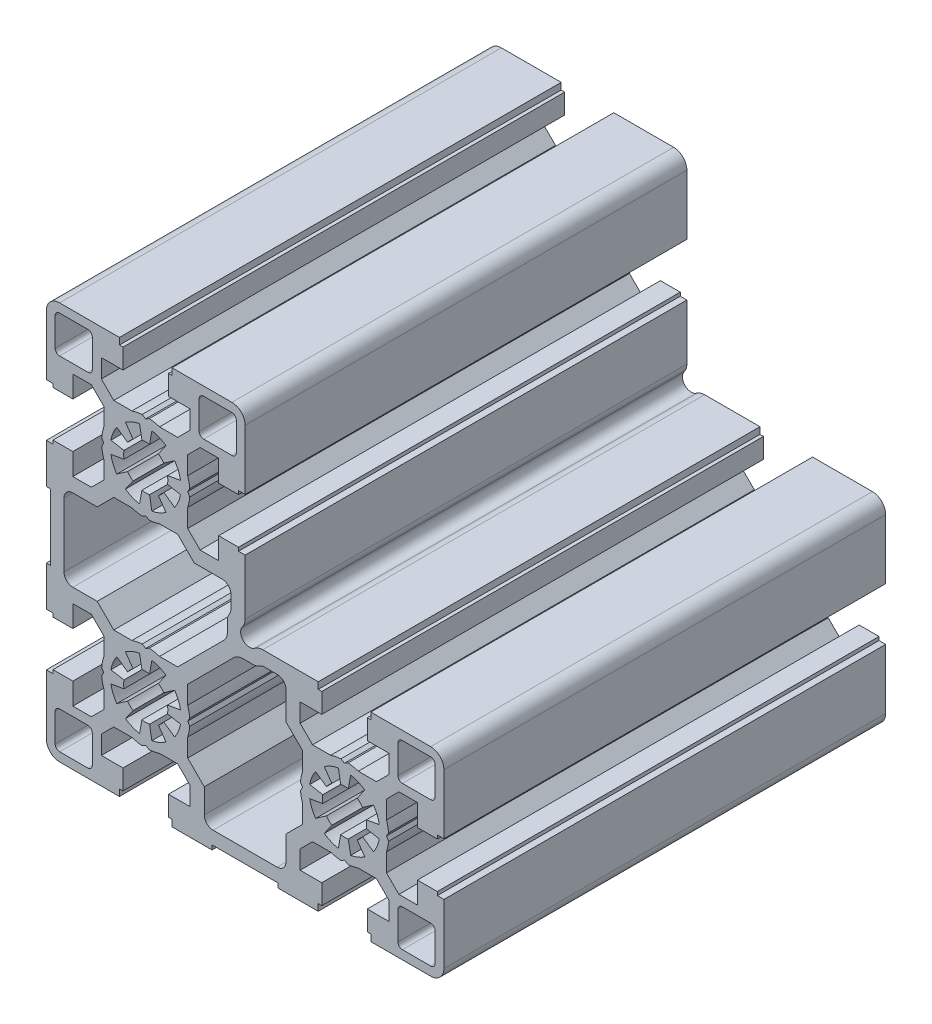
SolidWorks part; units mm, degrees
material "3.1355 (EN-AW 2024)"
ref_plane "Спереди" through (0, 0, 0) normal (0, 0, 1) x (1, 0, 0)
ref_plane "Сверху" through (0, 0, 0) normal (0, 1, 0) x (1, 0, 0)
ref_plane "Справа" through (0, 0, 0) normal (1, 0, 0) x (0, 0, -1)
sketch "Model" plane through (0, 0, 0) normal (0, 0, 1) x (1, 0, 0)
  line L512 (41.0101, -11.3899) -> (34.6101, -11.3899)
  line L513 (33.6101, -10.3899) -> (33.6101, -3.9899)
  line L514 (34.6101, -2.9899) -> (41.0101, -2.9899)
  line L515 (42.0101, -3.9899) -> (42.0101, -10.3899)
  line L516 (-43.9899, -42.9899) -> (-43.9899, -36.5899)
  line L517 (-42.9899, -35.5899) -> (-36.5899, -35.5899)
  line L518 (-35.5899, -36.5899) -> (-35.5899, -42.9899)
  line L519 (-36.5899, -43.9899) -> (-42.9899, -43.9899)
  line L520 (-19.3942, -20.6221) -> (-16.9367, -18.9013)
  line L521 (-15.6115, -22.1008) -> (-18.5659, -22.6217)
  line L522 (-18.5659, -24.3582) -> (-15.6115, -24.8791)
  line L523 (-16.9367, -28.0786) -> (-19.3942, -26.3578)
  line L524 (-20.6221, -27.5857) -> (-18.9013, -30.0432)
  line L525 (-22.1008, -31.3684) -> (-22.6217, -28.414)
  line L526 (-24.3582, -28.414) -> (-24.8791, -31.3684)
  line L527 (-28.0786, -30.0432) -> (-26.3578, -27.5857)
  line L528 (-27.5857, -26.3578) -> (-30.0432, -28.0786)
  line L529 (-31.3684, -24.8791) -> (-28.414, -24.3582)
  line L530 (-28.414, -22.6217) -> (-31.3684, -22.1008)
  line L531 (-30.0432, -18.9013) -> (-27.5857, -20.6221)
  line L532 (-26.3578, -19.3942) -> (-28.0786, -16.9367)
  line L533 (-24.8791, -15.6115) -> (-24.3582, -18.5659)
  line L534 (-22.6217, -18.5659) -> (-22.1008, -15.6115)
  line L535 (-18.9013, -16.9367) -> (-20.6221, -19.3942)
  line L536 (-10.3899, 42.0101) -> (-3.9899, 42.0101)
  line L537 (-2.9899, 41.0101) -> (-2.9899, 34.6101)
  line L538 (-3.9899, 33.6101) -> (-10.3899, 33.6101)
  line L539 (-11.3899, 34.6101) -> (-11.3899, 41.0101)
  line L540 (-20.6221, 17.4143) -> (-18.9013, 14.9568)
  line L541 (-22.1008, 13.6316) -> (-22.6217, 16.586)
  line L542 (-24.3582, 16.586) -> (-24.8791, 13.6316)
  line L543 (-28.0786, 14.9568) -> (-26.3578, 17.4143)
  line L544 (-27.5857, 18.6422) -> (-30.0432, 16.9214)
  line L545 (-31.3684, 20.1209) -> (-28.414, 20.6418)
  line L546 (-28.414, 22.3783) -> (-31.3684, 22.8992)
  line L547 (-30.0432, 26.0987) -> (-27.5857, 24.3779)
  line L548 (-26.3578, 25.6058) -> (-28.0786, 28.0633)
  line L549 (-24.8791, 29.3885) -> (-24.3582, 26.4341)
  line L550 (-22.6217, 26.4341) -> (-22.1008, 29.3885)
  line L551 (-18.9013, 28.0633) -> (-20.6221, 25.6058)
  line L552 (-19.3942, 24.3779) -> (-16.9367, 26.0987)
  line L553 (-15.6115, 22.8992) -> (-18.5659, 22.3783)
  line L554 (-18.5659, 20.6418) -> (-15.6115, 20.1209)
  line L555 (-16.9367, 16.9214) -> (-19.3942, 18.6422)
  line L556 (-42.9899, 42.0101) -> (-36.5899, 42.0101)
  line L557 (-35.5899, 41.0101) -> (-35.5899, 34.6101)
  line L558 (-36.5899, 33.6101) -> (-42.9899, 33.6101)
  line L559 (-43.9899, 34.6101) -> (-43.9899, 41.0101)
  line L560 (-13.9899, -16.2527) -> (-3.6059, -5.8686)
  line L561 (-1.4846, -4.9899) -> (0.9237, -4.9899)
  line L562 (1.916, -4.7264) -> (2.3937, -4.4535)
  line L563 (3.386, -4.1899) -> (6.2596, -4.1899)
  line L564 (8.2596, -6.1899) -> (8.2596, -12.5023)
  line L565 (8.2596, -12.5023) -> (12.0101, -16.2527)
  line L566 (12.0101, -16.2527) -> (12.0101, -20.3675)
  line L567 (11.5428, -22.6807) -> (12.0101, -23.4899)
  line L568 (12.0101, -23.4899) -> (11.5428, -24.2992)
  line L569 (12.0101, -26.6124) -> (12.0101, -30.7272)
  line L570 (12.0101, -30.7272) -> (8.2596, -34.4776)
  line L571 (8.2596, -34.4776) -> (8.2596, -39.9899)
  line L572 (6.2596, -41.9899) -> (-8.2399, -41.9899)
  line L573 (-10.2399, -39.9899) -> (-10.2399, -34.4772)
  line L574 (-10.2399, -34.4772) -> (-13.9899, -30.7272)
  line L575 (-13.9899, -30.7272) -> (-13.9899, -26.6124)
  line L576 (-13.5227, -24.2992) -> (-13.9899, -23.4899)
  line L577 (-13.9899, -23.4899) -> (-13.5227, -22.6807)
  line L578 (-13.9899, -20.3675) -> (-13.9899, -16.2527)
  line L579 (-23.4899, -13.9899) -> (-24.2992, -13.5227)
  line L580 (-26.6124, -13.9899) -> (-30.7272, -13.9899)
  line L581 (-30.7272, -13.9899) -> (-34.4772, -10.2399)
  line L582 (-34.4772, -10.2399) -> (-39.9899, -10.2399)
  line L583 (-41.9899, -8.2399) -> (-41.9899, 6.2596)
  line L584 (-39.9899, 8.2596) -> (-34.4776, 8.2596)
  line L585 (-34.4776, 8.2596) -> (-30.7272, 12.0101)
  line L586 (-30.7272, 12.0101) -> (-26.6124, 12.0101)
  line L587 (-24.2992, 11.5428) -> (-23.4899, 12.0101)
  line L588 (-23.4899, 12.0101) -> (-22.6807, 11.5428)
  line L589 (-20.3675, 12.0101) -> (-16.2527, 12.0101)
  line L590 (-16.2527, 12.0101) -> (-12.5023, 8.2596)
  line L591 (-12.5023, 8.2596) -> (-6.1899, 8.2596)
  line L592 (-4.1899, 6.2596) -> (-4.1899, 3.386)
  line L593 (-4.4535, 2.3937) -> (-4.7264, 1.916)
  line L594 (-4.9899, 0.9237) -> (-4.9899, -1.4846)
  line L595 (-5.8686, -3.6059) -> (-16.2527, -13.9899)
  line L596 (-16.2527, -13.9899) -> (-20.3675, -13.9899)
  line L597 (-22.6807, -13.5227) -> (-23.4899, -13.9899)
  line L598 (24.3779, -27.5857) -> (26.0987, -30.0432)
  line L599 (22.8992, -31.3684) -> (22.3783, -28.414)
  line L600 (20.6418, -28.414) -> (20.1209, -31.3684)
  line L601 (16.9214, -30.0432) -> (18.6422, -27.5857)
  line L602 (17.4143, -26.3578) -> (14.9568, -28.0786)
  line L603 (13.6316, -24.8791) -> (16.586, -24.3582)
  line L604 (16.586, -22.6217) -> (13.6316, -22.1008)
  line L605 (14.9568, -18.9013) -> (17.4143, -20.6221)
  line L606 (18.6422, -19.3942) -> (16.9214, -16.9367)
  line L607 (20.1209, -15.6115) -> (20.6418, -18.5659)
  line L608 (22.3783, -18.5659) -> (22.8992, -15.6115)
  line L609 (26.0987, -16.9367) -> (24.3779, -19.3942)
  line L610 (25.6058, -20.6221) -> (28.0633, -18.9013)
  line L611 (29.3885, -22.1008) -> (26.4341, -22.6217)
  line L612 (26.4341, -24.3582) -> (29.3885, -24.8791)
  line L613 (28.0633, -28.0786) -> (25.6058, -26.3578)
  line L614 (41.0101, -43.9899) -> (34.6101, -43.9899)
  line L615 (33.6101, -42.9899) -> (33.6101, -36.5899)
  line L616 (34.6101, -35.5899) -> (41.0101, -35.5899)
  line L617 (42.0101, -36.5899) -> (42.0101, -42.9899)
  line L618 (38.0101, -18.3399) -> (42.5101, -18.3399)
  line L619 (42.5101, -18.3399) -> (42.5101, -17.5399)
  line L620 (42.5101, -17.5399) -> (44.0101, -17.5399)
  line L621 (44.0101, -17.5399) -> (44.0101, -3.9897)
  line L622 (41.0101, -0.9899) -> (27.4601, -0.9899)
  line L623 (27.4601, -0.9899) -> (27.4601, -2.4899)
  line L624 (27.4601, -2.4899) -> (26.6601, -2.4899)
  line L625 (26.6601, -2.4899) -> (26.6601, -6.9899)
  line L626 (26.6601, -6.9899) -> (31.5601, -6.9899)
  line L627 (31.5601, -6.9899) -> (31.5601, -11.1772)
  line L628 (31.5601, -11.1772) -> (28.7473, -13.9899)
  line L629 (28.7473, -13.9899) -> (24.6325, -13.9899)
  line L630 (22.3193, -13.5227) -> (21.5101, -13.9899)
  line L631 (21.5101, -13.9899) -> (20.7008, -13.5227)
  line L632 (18.3876, -13.9899) -> (14.2728, -13.9899)
  line L633 (14.2728, -13.9899) -> (11.4601, -11.1772)
  line L634 (11.4601, -11.1772) -> (11.4601, -6.9899)
  line L635 (11.4601, -6.9899) -> (16.3601, -6.9899)
  line L636 (16.3601, -6.9899) -> (16.3601, -2.4899)
  line L637 (16.3601, -2.4899) -> (15.5601, -2.4899)
  line L638 (15.5601, -2.4899) -> (15.5601, -0.9899)
  line L639 (15.5601, -0.9899) -> (3.0134, -0.9899)
  line L640 (-0.9899, 3.0134) -> (-0.9899, 15.5601)
  line L641 (-0.9899, 15.5601) -> (-2.4899, 15.5601)
  line L642 (-2.4899, 15.5601) -> (-2.4899, 16.3601)
  line L643 (-2.4899, 16.3601) -> (-6.9899, 16.3601)
  line L644 (-6.9899, 16.3601) -> (-6.9899, 11.4601)
  line L645 (-6.9899, 11.4601) -> (-11.1772, 11.4601)
  line L646 (-11.1772, 11.4601) -> (-13.9899, 14.2728)
  line L647 (-13.9899, 14.2728) -> (-13.9899, 18.3876)
  line L648 (-13.5227, 20.7008) -> (-13.9899, 21.5101)
  line L649 (-13.9899, 21.5101) -> (-13.5227, 22.3193)
  line L650 (-13.9899, 24.6325) -> (-13.9899, 28.7473)
  line L651 (-13.9899, 28.7473) -> (-11.1772, 31.5601)
  line L652 (-11.1772, 31.5601) -> (-6.9899, 31.5601)
  line L653 (-6.9899, 31.5601) -> (-6.9899, 26.6601)
  line L654 (-6.9899, 26.6601) -> (-2.4899, 26.6601)
  line L655 (-2.4899, 26.6601) -> (-2.4899, 27.4601)
  line L656 (-2.4899, 27.4601) -> (-0.9899, 27.4601)
  line L657 (-0.9899, 27.4601) -> (-0.9899, 41.0101)
  line L658 (-3.9899, 44.0101) -> (-17.5399, 44.0101)
  line L659 (-17.5399, 44.0101) -> (-17.5399, 42.5101)
  line L660 (-17.5399, 42.5101) -> (-18.3399, 42.5101)
  line L661 (-18.3399, 42.5101) -> (-18.3399, 38.0101)
  line L662 (-18.3399, 38.0101) -> (-13.4399, 38.0101)
  line L663 (-13.4399, 38.0101) -> (-13.4399, 33.8228)
  line L664 (-13.4399, 33.8228) -> (-16.2527, 31.0101)
  line L665 (-16.2527, 31.0101) -> (-20.3675, 31.0101)
  line L666 (-22.6807, 31.4773) -> (-23.4899, 31.0101)
  line L667 (-23.4899, 31.0101) -> (-24.2992, 31.4773)
  line L668 (-26.6124, 31.0101) -> (-30.7272, 31.0101)
  line L669 (-30.7272, 31.0101) -> (-33.5399, 33.8228)
  line L670 (-33.5399, 33.8228) -> (-33.5399, 38.0101)
  line L671 (-33.5399, 38.0101) -> (-28.6399, 38.0101)
  line L672 (-28.6399, 38.0101) -> (-28.6399, 42.5101)
  line L673 (-28.6399, 42.5101) -> (-29.4399, 42.5101)
  line L674 (-29.4399, 42.5101) -> (-29.4399, 44.0101)
  line L675 (-29.4399, 44.0101) -> (-42.9899, 44.0101)
  line L676 (-45.9899, 41.0101) -> (-45.9899, 27.4601)
  line L677 (-45.9899, 27.4601) -> (-44.4899, 27.4601)
  line L678 (-44.4899, 27.4601) -> (-44.4899, 26.6601)
  line L679 (-44.4899, 26.6601) -> (-39.9899, 26.6601)
  line L680 (-39.9899, 26.6601) -> (-39.9899, 31.5601)
  line L681 (-39.9899, 31.5601) -> (-35.8027, 31.5601)
  line L682 (-35.8027, 31.5601) -> (-32.9899, 28.7473)
  line L683 (-32.9899, 28.7473) -> (-32.9899, 24.6325)
  line L684 (-33.4572, 22.3193) -> (-32.9899, 21.5101)
  line L685 (-32.9899, 21.5101) -> (-33.4572, 20.7008)
  line L686 (-32.9899, 18.3876) -> (-32.9899, 14.2728)
  line L687 (-32.9899, 14.2728) -> (-35.8027, 11.4601)
  line L688 (-35.8027, 11.4601) -> (-39.9899, 11.4601)
  line L689 (-39.9899, 11.4601) -> (-39.9899, 16.3601)
  line L690 (-39.9899, 16.3601) -> (-44.4899, 16.3601)
  line L691 (-44.4899, 16.3601) -> (-44.4899, 15.5601)
  line L692 (-44.4899, 15.5601) -> (-45.9899, 15.5601)
  line L693 (-45.9899, 15.5601) -> (-45.9899, 6.5101)
  line L694 (-45.9899, 6.5101) -> (-44.9899, 6.5101)
  line L695 (-44.9899, 6.5101) -> (-44.9899, -8.4899)
  line L696 (-44.9899, -8.4899) -> (-45.9899, -8.4899)
  line L697 (-45.9899, -8.4899) -> (-45.9899, -17.5399)
  line L698 (-45.9899, -17.5399) -> (-44.4899, -17.5399)
  line L699 (-44.4899, -17.5399) -> (-44.4899, -18.3399)
  line L700 (-44.4899, -18.3399) -> (-39.9899, -18.3399)
  line L701 (-39.9899, -18.3399) -> (-39.9899, -13.4399)
  line L702 (-39.9899, -13.4399) -> (-35.8027, -13.4399)
  line L703 (-35.8027, -13.4399) -> (-32.9899, -16.2527)
  line L704 (-32.9899, -16.2527) -> (-32.9899, -20.3675)
  line L705 (-33.4576, -22.6807) -> (-32.9904, -23.4899)
  line L706 (-32.9904, -23.4899) -> (-33.4576, -24.2992)
  line L707 (-32.9899, -26.6138) -> (-32.9899, -30.7272)
  line L708 (-32.9899, -30.7272) -> (-35.8027, -33.5399)
  line L709 (-35.8027, -33.5399) -> (-39.9899, -33.5399)
  line L710 (-39.9899, -33.5399) -> (-39.9899, -28.6399)
  line L711 (-39.9899, -28.6399) -> (-44.4899, -28.6399)
  line L712 (-44.4899, -28.6399) -> (-44.4899, -29.4399)
  line L713 (-44.4899, -29.4399) -> (-45.9899, -29.4399)
  line L714 (-45.9899, -29.4399) -> (-45.9899, -42.9899)
  line L715 (-42.9899, -45.9899) -> (-29.4399, -45.9899)
  line L716 (-29.4399, -45.9899) -> (-29.4399, -44.4899)
  line L717 (-29.4399, -44.4899) -> (-28.6399, -44.4899)
  line L718 (-28.6399, -44.4899) -> (-28.6399, -39.9899)
  line L719 (-28.6399, -39.9899) -> (-33.5399, -39.9899)
  line L720 (-33.5399, -39.9899) -> (-33.5399, -35.8027)
  line L721 (-33.5399, -35.8027) -> (-30.7272, -32.9899)
  line L722 (-30.7272, -32.9899) -> (-26.6124, -32.9899)
  line L723 (-24.2992, -33.4572) -> (-23.4899, -32.9899)
  line L724 (-23.4899, -32.9899) -> (-22.6807, -33.4572)
  line L725 (-20.3675, -32.9899) -> (-16.2527, -32.9899)
  line L726 (-16.2527, -32.9899) -> (-13.4399, -35.8027)
  line L727 (-13.4399, -35.8027) -> (-13.4399, -39.9899)
  line L728 (-13.4399, -39.9899) -> (-18.3399, -39.9899)
  line L729 (-18.3399, -39.9899) -> (-18.3399, -44.4899)
  line L730 (-18.3399, -44.4899) -> (-17.5399, -44.4899)
  line L731 (-17.5399, -44.4899) -> (-17.5399, -45.9899)
  line L732 (-17.5399, -45.9899) -> (-8.4899, -45.9899)
  line L733 (-8.4899, -45.9899) -> (-8.4899, -44.9899)
  line L734 (-8.4899, -44.9899) -> (6.5101, -44.9899)
  line L735 (6.5101, -44.9899) -> (6.5101, -45.9899)
  line L736 (6.5101, -45.9899) -> (15.5601, -45.9899)
  line L737 (15.5601, -45.9899) -> (15.5601, -44.4899)
  line L738 (15.5601, -44.4899) -> (16.3601, -44.4899)
  line L739 (16.3601, -44.4899) -> (16.3601, -39.9899)
  line L740 (16.3601, -39.9899) -> (11.4601, -39.9899)
  line L741 (11.4601, -39.9899) -> (11.4601, -35.8027)
  line L742 (11.4601, -35.8027) -> (14.2728, -32.9899)
  line L743 (14.2728, -32.9899) -> (18.3876, -32.9899)
  line L744 (20.7008, -33.4572) -> (21.5101, -32.9899)
  line L745 (21.5101, -32.9899) -> (22.3193, -33.4572)
  line L746 (24.6325, -32.9899) -> (28.7473, -32.9899)
  line L747 (28.7473, -32.9899) -> (31.5601, -35.8027)
  line L748 (31.5601, -35.8027) -> (31.5601, -39.9899)
  line L749 (31.5601, -39.9899) -> (26.6601, -39.9899)
  line L750 (26.6601, -39.9899) -> (26.6601, -44.4899)
  line L751 (26.6601, -44.4899) -> (27.4601, -44.4899)
  line L752 (27.4601, -44.4899) -> (27.4601, -45.9899)
  line L753 (27.4601, -45.9899) -> (41.0101, -45.9899)
  line L754 (44.0101, -42.9899) -> (44.0101, -29.4399)
  line L755 (44.0101, -29.4399) -> (42.5101, -29.4399)
  line L756 (42.5101, -29.4399) -> (42.5101, -28.6399)
  line L757 (42.5101, -28.6399) -> (38.0101, -28.6399)
  line L758 (38.0101, -28.6399) -> (38.0101, -33.5399)
  line L759 (38.0101, -33.5399) -> (33.8228, -33.5399)
  line L760 (33.8228, -33.5399) -> (31.0101, -30.7272)
  line L761 (31.0101, -30.7272) -> (31.0101, -26.6124)
  line L762 (31.4773, -24.2992) -> (31.0101, -23.4899)
  line L763 (31.0101, -23.4899) -> (31.4773, -22.6807)
  line L764 (31.0101, -20.3675) -> (31.0101, -16.2527)
  line L765 (31.0101, -16.2527) -> (33.8228, -13.4399)
  line L766 (33.8228, -13.4399) -> (38.0101, -13.4399)
  line L767 (38.0101, -13.4399) -> (38.0101, -18.3399)
  arc A224 (33.6101, -10.3899) -> (34.6101, -11.3899) centre (34.6101, -10.3899) ccw
  arc A225 (34.6101, -2.9899) -> (33.6101, -3.9899) centre (34.6101, -3.9899) ccw
  arc A226 (42.0101, -3.9899) -> (41.0101, -2.9899) centre (41.0101, -3.9899) ccw
  arc A227 (41.0101, -11.3899) -> (42.0101, -10.3899) centre (41.0101, -10.3899) ccw
  arc A228 (-42.9899, -35.5899) -> (-43.9899, -36.5899) centre (-42.9899, -36.5899) ccw
  arc A229 (-35.5899, -36.5899) -> (-36.5899, -35.5899) centre (-36.5899, -36.5899) ccw
  arc A230 (-36.5899, -43.9899) -> (-35.5899, -42.9899) centre (-36.5899, -42.9899) ccw
  arc A231 (-43.9899, -42.9899) -> (-42.9899, -43.9899) centre (-42.9899, -42.9899) ccw
  arc A232 (-15.6115, -22.1008) -> (-16.9367, -18.9013) centre (-23.4899, -23.4899) ccw
  arc A233 (-18.5659, -24.3582) -> (-18.5659, -22.6217) centre (-23.4899, -23.4899) ccw
  arc A234 (-16.9367, -28.0786) -> (-15.6115, -24.8791) centre (-23.4899, -23.4899) ccw
  arc A235 (-20.6221, -27.5857) -> (-19.3942, -26.3578) centre (-23.4899, -23.4899) ccw
  arc A236 (-22.1008, -31.3684) -> (-18.9013, -30.0432) centre (-23.4899, -23.4899) ccw
  arc A237 (-24.3582, -28.414) -> (-22.6217, -28.414) centre (-23.4899, -23.4899) ccw
  arc A238 (-28.0786, -30.0432) -> (-24.8791, -31.3684) centre (-23.4899, -23.4899) ccw
  arc A239 (-27.5857, -26.3578) -> (-26.3578, -27.5857) centre (-23.4899, -23.4899) ccw
  arc A240 (-31.3684, -24.8791) -> (-30.0432, -28.0786) centre (-23.4899, -23.4899) ccw
  arc A241 (-28.414, -22.6217) -> (-28.414, -24.3582) centre (-23.4899, -23.4899) ccw
  arc A242 (-30.0432, -18.9013) -> (-31.3684, -22.1008) centre (-23.4899, -23.4899) ccw
  arc A243 (-26.3578, -19.3942) -> (-27.5857, -20.6221) centre (-23.4899, -23.4899) ccw
  arc A244 (-24.8791, -15.6115) -> (-28.0786, -16.9367) centre (-23.4899, -23.4899) ccw
  arc A245 (-22.6217, -18.5659) -> (-24.3582, -18.5659) centre (-23.4899, -23.4899) ccw
  arc A246 (-18.9013, -16.9367) -> (-22.1008, -15.6115) centre (-23.4899, -23.4899) ccw
  arc A247 (-19.3942, -20.6221) -> (-20.6221, -19.3942) centre (-23.4899, -23.4899) ccw
  arc A248 (-2.9899, 41.0101) -> (-3.9899, 42.0101) centre (-3.9899, 41.0101) ccw
  arc A249 (-3.9899, 33.6101) -> (-2.9899, 34.6101) centre (-3.9899, 34.6101) ccw
  arc A250 (-11.3899, 34.6101) -> (-10.3899, 33.6101) centre (-10.3899, 34.6101) ccw
  arc A251 (-10.3899, 42.0101) -> (-11.3899, 41.0101) centre (-10.3899, 41.0101) ccw
  arc A252 (-22.1008, 13.6316) -> (-18.9013, 14.9568) centre (-23.4899, 21.5101) ccw
  arc A253 (-24.3582, 16.586) -> (-22.6217, 16.586) centre (-23.4899, 21.5101) ccw
  arc A254 (-28.0786, 14.9568) -> (-24.8791, 13.6316) centre (-23.4899, 21.5101) ccw
  arc A255 (-27.5857, 18.6422) -> (-26.3578, 17.4143) centre (-23.4899, 21.5101) ccw
  arc A256 (-31.3684, 20.1209) -> (-30.0432, 16.9214) centre (-23.4899, 21.5101) ccw
  arc A257 (-28.414, 22.3783) -> (-28.414, 20.6418) centre (-23.4899, 21.5101) ccw
  arc A258 (-30.0432, 26.0987) -> (-31.3684, 22.8992) centre (-23.4899, 21.5101) ccw
  arc A259 (-26.3578, 25.6058) -> (-27.5857, 24.3779) centre (-23.4899, 21.5101) ccw
  arc A260 (-24.8791, 29.3885) -> (-28.0786, 28.0633) centre (-23.4899, 21.5101) ccw
  arc A261 (-22.6217, 26.4341) -> (-24.3582, 26.4341) centre (-23.4899, 21.5101) ccw
  arc A262 (-18.9013, 28.0633) -> (-22.1008, 29.3885) centre (-23.4899, 21.5101) ccw
  arc A263 (-19.3942, 24.3779) -> (-20.6221, 25.6058) centre (-23.4899, 21.5101) ccw
  arc A264 (-15.6115, 22.8992) -> (-16.9367, 26.0987) centre (-23.4899, 21.5101) ccw
  arc A265 (-18.5659, 20.6418) -> (-18.5659, 22.3783) centre (-23.4899, 21.5101) ccw
  arc A266 (-16.9367, 16.9214) -> (-15.6115, 20.1209) centre (-23.4899, 21.5101) ccw
  arc A267 (-20.6221, 17.4143) -> (-19.3942, 18.6422) centre (-23.4899, 21.5101) ccw
  arc A268 (-35.5899, 41.0101) -> (-36.5899, 42.0101) centre (-36.5899, 41.0101) ccw
  arc A269 (-36.5899, 33.6101) -> (-35.5899, 34.6101) centre (-36.5899, 34.6101) ccw
  arc A270 (-43.9899, 34.6101) -> (-42.9899, 33.6101) centre (-42.9899, 34.6101) ccw
  arc A271 (-42.9899, 42.0101) -> (-43.9899, 41.0101) centre (-42.9899, 41.0101) ccw
  arc A272 (-1.4846, -4.9899) -> (-3.6059, -5.8686) centre (-1.4846, -7.9899) ccw
  arc A273 (0.9237, -4.9899) -> (1.916, -4.7264) centre (0.9237, -2.9899) ccw
  arc A274 (3.386, -4.1899) -> (2.3937, -4.4535) centre (3.386, -6.1899) ccw
  arc A275 (8.2596, -6.1899) -> (6.2596, -4.1899) centre (6.2596, -6.1899) ccw
  arc A276 (12.0101, -20.3675) -> (11.5428, -22.6807) centre (21.5101, -23.4899) ccw
  arc A277 (11.5428, -24.2992) -> (12.0101, -26.6124) centre (21.5101, -23.4899) ccw
  arc A278 (6.2596, -41.9899) -> (8.2596, -39.9899) centre (6.2596, -39.9899) ccw
  arc A279 (-10.2399, -39.9899) -> (-8.2399, -41.9899) centre (-8.2399, -39.9899) ccw
  arc A280 (-13.9899, -26.6124) -> (-13.5227, -24.2992) centre (-23.4899, -23.4899) ccw
  arc A281 (-13.5227, -22.6807) -> (-13.9899, -20.3675) centre (-23.4899, -23.4899) ccw
  arc A282 (-24.2992, -13.5227) -> (-26.6124, -13.9899) centre (-23.4899, -23.4899) ccw
  arc A283 (-41.9899, -8.2399) -> (-39.9899, -10.2399) centre (-39.9899, -8.2399) ccw
  arc A284 (-39.9899, 8.2596) -> (-41.9899, 6.2596) centre (-39.9899, 6.2596) ccw
  arc A285 (-26.6124, 12.0101) -> (-24.2992, 11.5428) centre (-23.4899, 21.5101) ccw
  arc A286 (-22.6807, 11.5428) -> (-20.3675, 12.0101) centre (-23.4899, 21.5101) ccw
  arc A287 (-4.1899, 6.2596) -> (-6.1899, 8.2596) centre (-6.1899, 6.2596) ccw
  arc A288 (-4.4535, 2.3937) -> (-4.1899, 3.386) centre (-6.1899, 3.386) ccw
  arc A289 (-4.7264, 1.916) -> (-4.9899, 0.9237) centre (-2.9899, 0.9237) ccw
  arc A290 (-5.8686, -3.6059) -> (-4.9899, -1.4846) centre (-7.9899, -1.4846) ccw
  arc A291 (-20.3675, -13.9899) -> (-22.6807, -13.5227) centre (-23.4899, -23.4899) ccw
  arc A292 (22.8992, -31.3684) -> (26.0987, -30.0432) centre (21.5101, -23.4899) ccw
  arc A293 (20.6418, -28.414) -> (22.3783, -28.414) centre (21.5101, -23.4899) ccw
  arc A294 (16.9214, -30.0432) -> (20.1209, -31.3684) centre (21.5101, -23.4899) ccw
  arc A295 (17.4143, -26.3578) -> (18.6422, -27.5857) centre (21.5101, -23.4899) ccw
  arc A296 (13.6316, -24.8791) -> (14.9568, -28.0786) centre (21.5101, -23.4899) ccw
  arc A297 (16.586, -22.6217) -> (16.586, -24.3582) centre (21.5101, -23.4899) ccw
  arc A298 (14.9568, -18.9013) -> (13.6316, -22.1008) centre (21.5101, -23.4899) ccw
  arc A299 (18.6422, -19.3942) -> (17.4143, -20.6221) centre (21.5101, -23.4899) ccw
  arc A300 (20.1209, -15.6115) -> (16.9214, -16.9367) centre (21.5101, -23.4899) ccw
  arc A301 (22.3783, -18.5659) -> (20.6418, -18.5659) centre (21.5101, -23.4899) ccw
  arc A302 (26.0987, -16.9367) -> (22.8992, -15.6115) centre (21.5101, -23.4899) ccw
  arc A303 (25.6058, -20.6221) -> (24.3779, -19.3942) centre (21.5101, -23.4899) ccw
  arc A304 (29.3885, -22.1008) -> (28.0633, -18.9013) centre (21.5101, -23.4899) ccw
  arc A305 (26.4341, -24.3582) -> (26.4341, -22.6217) centre (21.5101, -23.4899) ccw
  arc A306 (28.0633, -28.0786) -> (29.3885, -24.8791) centre (21.5101, -23.4899) ccw
  arc A307 (24.3779, -27.5857) -> (25.6058, -26.3578) centre (21.5101, -23.4899) ccw
  arc A308 (33.6101, -42.9899) -> (34.6101, -43.9899) centre (34.6101, -42.9899) ccw
  arc A309 (34.6101, -35.5899) -> (33.6101, -36.5899) centre (34.6101, -36.5899) ccw
  arc A310 (42.0101, -36.5899) -> (41.0101, -35.5899) centre (41.0101, -36.5899) ccw
  arc A311 (41.0101, -43.9899) -> (42.0101, -42.9899) centre (41.0101, -42.9899) ccw
  arc A312 (44.0101, -3.9897) -> (41.0101, -0.9899) centre (41.0101, -3.9899) ccw
  arc A313 (24.6325, -13.9899) -> (22.3193, -13.5227) centre (21.5101, -23.4899) ccw
  arc A314 (20.7008, -13.5227) -> (18.3876, -13.9899) centre (21.5101, -23.4899) ccw
  arc A315 (3.0134, -0.9899) -> (1.2053, -1.596) centre (3.0134, -3.9899) ccw
  arc A316 (-1.596, 1.2053) -> (1.2053, -1.596) centre (0, 0) ccw
  arc A317 (-1.596, 1.2053) -> (-0.9899, 3.0134) centre (-3.9899, 3.0134) ccw
  arc A318 (-13.9899, 18.3876) -> (-13.5227, 20.7008) centre (-23.4899, 21.5101) ccw
  arc A319 (-13.5227, 22.3193) -> (-13.9899, 24.6325) centre (-23.4899, 21.5101) ccw
  arc A320 (-0.9899, 41.0101) -> (-3.9899, 44.0101) centre (-3.9899, 41.0101) ccw
  arc A321 (-20.3675, 31.0101) -> (-22.6807, 31.4773) centre (-23.4899, 21.5101) ccw
  arc A322 (-24.2992, 31.4773) -> (-26.6124, 31.0101) centre (-23.4899, 21.5101) ccw
  arc A323 (-42.9899, 44.0101) -> (-45.9899, 41.0101) centre (-42.9899, 41.0101) ccw
  arc A324 (-32.9899, 24.6325) -> (-33.4572, 22.3193) centre (-23.4899, 21.5101) ccw
  arc A325 (-33.4572, 20.7008) -> (-32.9899, 18.3876) centre (-23.4899, 21.5101) ccw
  arc A326 (-32.9899, -20.3675) -> (-33.4576, -22.6807) centre (-23.5411, -23.4815) ccw
  arc A327 (-33.4576, -24.2992) -> (-32.9899, -26.6138) centre (-23.4904, -23.4899) ccw
  arc A328 (-45.9899, -42.9899) -> (-42.9899, -45.9899) centre (-42.9899, -42.9899) ccw
  arc A329 (-26.6124, -32.9899) -> (-24.2992, -33.4572) centre (-23.4899, -23.4899) ccw
  arc A330 (-22.6807, -33.4572) -> (-20.3675, -32.9899) centre (-23.4899, -23.4899) ccw
  arc A331 (18.3876, -32.9899) -> (20.7008, -33.4572) centre (21.51, -23.4904) ccw
  arc A332 (22.3193, -33.4572) -> (24.6325, -32.9899) centre (21.5101, -23.4899) ccw
  arc A333 (41.0101, -45.9899) -> (44.0101, -42.9899) centre (41.0101, -42.9899) ccw
  arc A334 (31.0101, -26.6124) -> (31.4773, -24.2992) centre (21.5101, -23.4899) ccw
  arc A335 (31.4773, -22.6807) -> (31.0101, -20.3675) centre (21.5101, -23.4899) ccw
  dimension "D1" = 45
  dimension "D2" = 90
  dimension "D3" = 90
extrude "Бобышка-Вытянуть1" add sketch "Model" against normal blind 100
